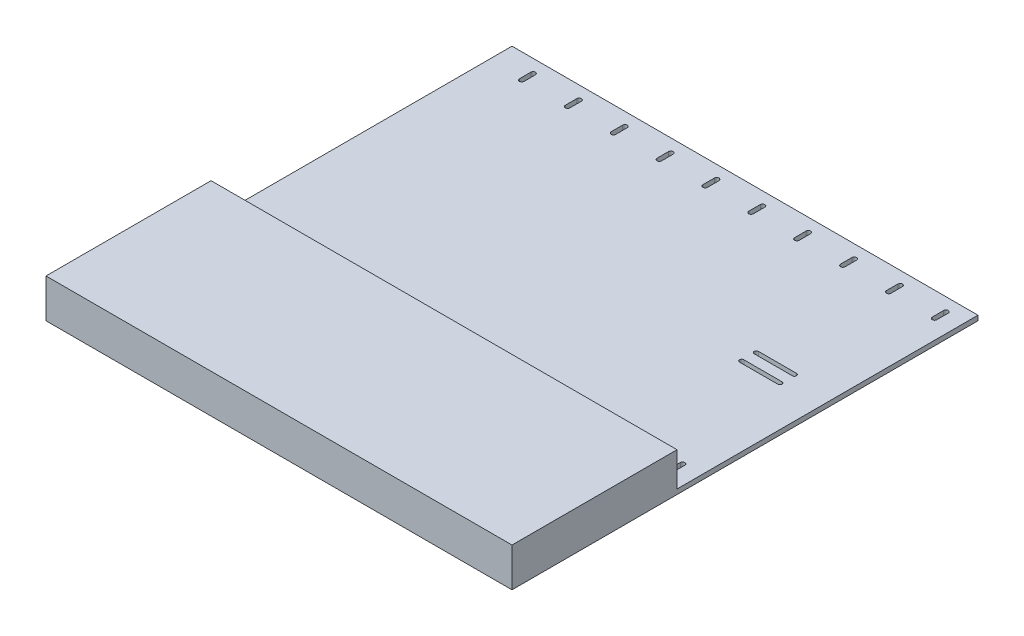
SolidWorks part; units mm, degrees
ref_plane "Front Plane" through (0, 0, 0) normal (0, 0, 1) x (1, 0, 0)
ref_plane "Top Plane" through (0, 0, 0) normal (0, 1, 0) x (1, 0, 0)
ref_plane "Right Plane" through (0, 0, 0) normal (1, 0, 0) x (0, 0, -1)
sketch "Sketch1" plane through (0, 0, 0) normal (0, 1, 0) x (1, 0, 0)
  line L0 (0, 369.15) -> (609.6, 369.15) construction
  line L1 (0, 0) -> (609.6, 0)
  line L2 (0, 0) -> (0, 393.7)
  line L3 (0, 393.7) -> (609.6, 393.7)
  line L4 (609.6, 0) -> (609.6, 393.7)
  line L5 (0, 24.55) -> (609.6, 24.55) construction
  line L6 (584.8, 32.05) -> (584.8, 17.05) construction
  line L9 (587.8, 32.05) -> (587.8, 17.05)
  line L10 (581.8, 32.05) -> (581.8, 17.05)
  line L11 (524.8, 32.05) -> (524.8, 17.05) construction
  line L12 (527.8, 32.05) -> (527.8, 17.05)
  line L13 (521.8, 32.05) -> (521.8, 17.05)
  line L14 (464.8, 32.05) -> (464.8, 17.05) construction
  line L15 (467.8, 32.05) -> (467.8, 17.05)
  line L16 (461.8, 32.05) -> (461.8, 17.05)
  line L17 (404.8, 32.05) -> (404.8, 17.05) construction
  line L18 (407.8, 32.05) -> (407.8, 17.05)
  line L19 (401.8, 32.05) -> (401.8, 17.05)
  line L20 (344.8, 32.05) -> (344.8, 17.05) construction
  line L21 (347.8, 32.05) -> (347.8, 17.05)
  line L22 (341.8, 32.05) -> (341.8, 17.05)
  line L23 (284.8, 32.05) -> (284.8, 17.05) construction
  line L24 (287.8, 32.05) -> (287.8, 17.05)
  line L25 (281.8, 32.05) -> (281.8, 17.05)
  line L26 (224.8, 32.05) -> (224.8, 17.05) construction
  line L27 (227.8, 32.05) -> (227.8, 17.05)
  line L28 (221.8, 32.05) -> (221.8, 17.05)
  line L29 (164.8, 32.05) -> (164.8, 17.05) construction
  line L30 (167.8, 32.05) -> (167.8, 17.05)
  line L31 (161.8, 32.05) -> (161.8, 17.05)
  line L32 (104.8, 32.05) -> (104.8, 17.05) construction
  line L33 (107.8, 32.05) -> (107.8, 17.05)
  line L34 (101.8, 32.05) -> (101.8, 17.05)
  line L35 (44.8, 32.05) -> (44.8, 17.05) construction
  line L36 (47.8, 32.05) -> (47.8, 17.05)
  line L37 (41.8, 32.05) -> (41.8, 17.05)
  line L38 (524.8, 376.65) -> (524.8, 361.65) construction
  line L39 (527.8, 376.65) -> (527.8, 361.65)
  line L40 (521.8, 376.65) -> (521.8, 361.65)
  line L41 (464.8, 376.65) -> (464.8, 361.65) construction
  line L42 (467.8, 376.65) -> (467.8, 361.65)
  line L43 (461.8, 376.65) -> (461.8, 361.65)
  line L44 (404.8, 376.65) -> (404.8, 361.65) construction
  line L45 (407.8, 376.65) -> (407.8, 361.65)
  line L46 (401.8, 376.65) -> (401.8, 361.65)
  line L47 (344.8, 376.65) -> (344.8, 361.65) construction
  line L48 (347.8, 376.65) -> (347.8, 361.65)
  line L49 (341.8, 376.65) -> (341.8, 361.65)
  line L50 (284.8, 376.65) -> (284.8, 361.65) construction
  line L51 (287.8, 376.65) -> (287.8, 361.65)
  line L52 (281.8, 376.65) -> (281.8, 361.65)
  line L53 (224.8, 376.65) -> (224.8, 361.65) construction
  line L54 (227.8, 376.65) -> (227.8, 361.65)
  line L55 (221.8, 376.65) -> (221.8, 361.65)
  line L56 (164.8, 376.65) -> (164.8, 361.65) construction
  line L57 (167.8, 376.65) -> (167.8, 361.65)
  line L58 (161.8, 376.65) -> (161.8, 361.65)
  line L59 (104.8, 376.65) -> (104.8, 361.65) construction
  line L60 (107.8, 376.65) -> (107.8, 361.65)
  line L61 (101.8, 376.65) -> (101.8, 361.65)
  line L62 (44.8, 376.65) -> (44.8, 361.65) construction
  line L63 (47.8, 376.65) -> (47.8, 361.65)
  line L64 (41.8, 376.65) -> (41.8, 361.65)
  line L65 (584.8, 376.65) -> (584.8, 361.65) construction
  line L66 (587.8, 376.65) -> (587.8, 361.65)
  line L67 (581.8, 376.65) -> (581.8, 361.65)
  line L68 (609.6, 187.325) -> (0, 187.325) construction
  line L69 (0, 206.375) -> (609.6, 206.375) construction
  line L70 (506.85, 206.375) -> (556.85, 206.375) construction
  line L71 (506.85, 209.125) -> (556.85, 209.125)
  line L72 (506.85, 203.625) -> (556.85, 203.625)
  line L73 (506.85, 187.325) -> (556.85, 187.325) construction
  line L74 (506.85, 190.075) -> (556.85, 190.075)
  line L75 (506.85, 184.575) -> (556.85, 184.575)
  arc A22 (587.8, 32.05) -> (581.8, 32.05) centre (584.8, 32.05) ccw
  arc A23 (581.8, 17.05) -> (587.8, 17.05) centre (584.8, 17.05) ccw
  arc A24 (506.85, 209.125) -> (506.85, 203.625) centre (506.85, 206.375) ccw
  arc A25 (527.8, 32.05) -> (521.8, 32.05) centre (524.8, 32.05) ccw
  arc A26 (521.8, 17.05) -> (527.8, 17.05) centre (524.8, 17.05) ccw
  arc A27 (467.8, 32.05) -> (461.8, 32.05) centre (464.8, 32.05) ccw
  arc A28 (461.8, 17.05) -> (467.8, 17.05) centre (464.8, 17.05) ccw
  arc A29 (407.8, 32.05) -> (401.8, 32.05) centre (404.8, 32.05) ccw
  arc A30 (401.8, 17.05) -> (407.8, 17.05) centre (404.8, 17.05) ccw
  arc A31 (347.8, 32.05) -> (341.8, 32.05) centre (344.8, 32.05) ccw
  arc A32 (341.8, 17.05) -> (347.8, 17.05) centre (344.8, 17.05) ccw
  arc A33 (287.8, 32.05) -> (281.8, 32.05) centre (284.8, 32.05) ccw
  arc A34 (281.8, 17.05) -> (287.8, 17.05) centre (284.8, 17.05) ccw
  arc A35 (227.8, 32.05) -> (221.8, 32.05) centre (224.8, 32.05) ccw
  arc A36 (221.8, 17.05) -> (227.8, 17.05) centre (224.8, 17.05) ccw
  arc A37 (167.8, 32.05) -> (161.8, 32.05) centre (164.8, 32.05) ccw
  arc A38 (161.8, 17.05) -> (167.8, 17.05) centre (164.8, 17.05) ccw
  arc A39 (107.8, 32.05) -> (101.8, 32.05) centre (104.8, 32.05) ccw
  arc A40 (101.8, 17.05) -> (107.8, 17.05) centre (104.8, 17.05) ccw
  arc A41 (47.8, 32.05) -> (41.8, 32.05) centre (44.8, 32.05) ccw
  arc A42 (41.8, 17.05) -> (47.8, 17.05) centre (44.8, 17.05) ccw
  arc A43 (527.8, 376.65) -> (521.8, 376.65) centre (524.8, 376.65) ccw
  arc A44 (521.8, 361.65) -> (527.8, 361.65) centre (524.8, 361.65) ccw
  arc A45 (467.8, 376.65) -> (461.8, 376.65) centre (464.8, 376.65) ccw
  arc A46 (461.8, 361.65) -> (467.8, 361.65) centre (464.8, 361.65) ccw
  arc A47 (407.8, 376.65) -> (401.8, 376.65) centre (404.8, 376.65) ccw
  arc A48 (401.8, 361.65) -> (407.8, 361.65) centre (404.8, 361.65) ccw
  arc A49 (347.8, 376.65) -> (341.8, 376.65) centre (344.8, 376.65) ccw
  arc A50 (341.8, 361.65) -> (347.8, 361.65) centre (344.8, 361.65) ccw
  arc A51 (287.8, 376.65) -> (281.8, 376.65) centre (284.8, 376.65) ccw
  arc A52 (281.8, 361.65) -> (287.8, 361.65) centre (284.8, 361.65) ccw
  arc A53 (227.8, 376.65) -> (221.8, 376.65) centre (224.8, 376.65) ccw
  arc A54 (221.8, 361.65) -> (227.8, 361.65) centre (224.8, 361.65) ccw
  arc A55 (167.8, 376.65) -> (161.8, 376.65) centre (164.8, 376.65) ccw
  arc A56 (161.8, 361.65) -> (167.8, 361.65) centre (164.8, 361.65) ccw
  arc A57 (107.8, 376.65) -> (101.8, 376.65) centre (104.8, 376.65) ccw
  arc A58 (101.8, 361.65) -> (107.8, 361.65) centre (104.8, 361.65) ccw
  arc A59 (47.8, 376.65) -> (41.8, 376.65) centre (44.8, 376.65) ccw
  arc A60 (41.8, 361.65) -> (47.8, 361.65) centre (44.8, 361.65) ccw
  arc A61 (587.8, 376.65) -> (581.8, 376.65) centre (584.8, 376.65) ccw
  arc A62 (581.8, 361.65) -> (587.8, 361.65) centre (584.8, 361.65) ccw
  arc A63 (556.85, 203.625) -> (556.85, 209.125) centre (556.85, 206.375) ccw
  arc A64 (506.85, 190.075) -> (506.85, 184.575) centre (506.85, 187.325) ccw
  arc A65 (556.85, 184.575) -> (556.85, 190.075) centre (556.85, 187.325) ccw
  point P12 (524.8, 24.55)
  point P19 (464.8, 24.55)
  point P26 (404.8, 24.55)
  point P32 (531.85, 206.375)
  point P38 (531.85, 187.325)
  point P51 (584.8, 24.55)
  point P63 (344.8, 24.55)
  point P70 (284.8, 24.55)
  point P77 (224.8, 24.55)
  point P84 (164.8, 24.55)
  point P91 (104.8, 24.55)
  point P98 (44.8, 24.55)
  point P105 (524.8, 369.15)
  point P112 (464.8, 369.15)
  point P119 (404.8, 369.15)
  point P126 (344.8, 369.15)
  point P133 (284.8, 369.15)
  point P140 (224.8, 369.15)
  point P147 (164.8, 369.15)
  point P154 (104.8, 369.15)
  point P161 (44.8, 369.15)
  point P168 (584.8, 369.15)
  dimension "D5" = 60
  dimension "D12" = 15
  dimension "D15" = 50
  dimension "D1" = 393.7
  dimension "D2" = 609.6
  dimension "D3" = 10
  dimension "D4" = 2
  dimension "D8" = 187.325
  dimension "D9" = 5.5
  dimension "D10" = 24.55
  dimension "D11" = 24.55
  dimension "D13" = 6
  dimension "D14" = 24.8
  dimension "D6" = 344.6
  dimension "D7" = 187.325
  dimension "D16" = 50
extrude "Boss-Extrude1" add sketch "Sketch1" along normal blind 6.35
sketch "Sketch2" plane through (0, 0, 0) normal (0, -1, 0) x (1, 0, 0)
  line L1 (609.6, 0) -> (0, 0)
  line L2 (609.6, 0) -> (609.6, 215.9)
  line L3 (609.6, 215.9) -> (0, 215.9)
  line L4 (0, 0) -> (0, 215.9)
  dimension "D1" = 215.9
extrude "Boss-Extrude2" add sketch "Sketch2" against normal blind 50.8
